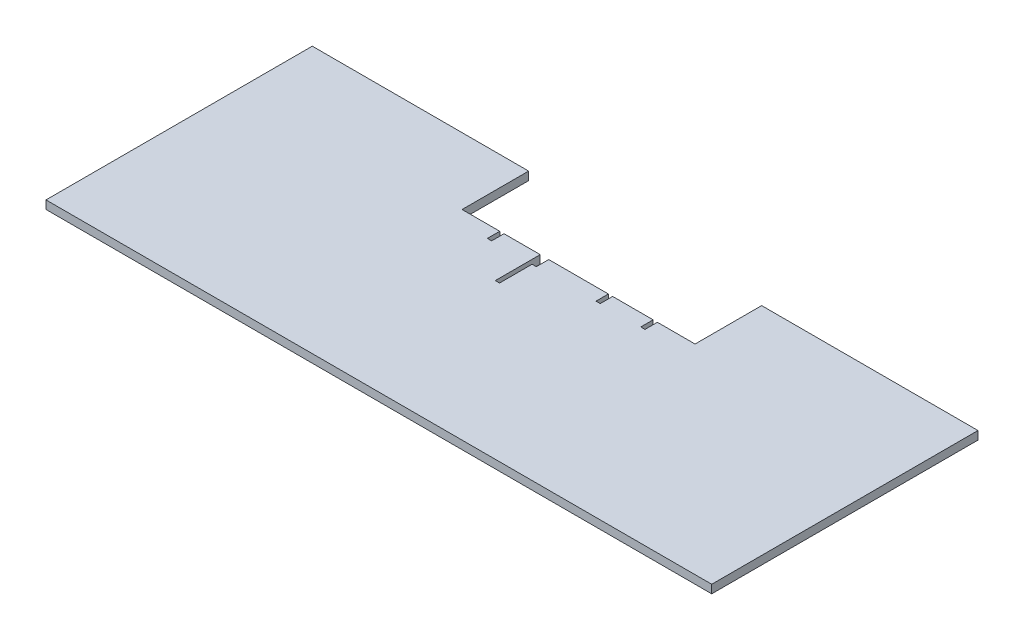
SolidWorks part; units mm, degrees
material "Depron"
ref_plane "Front Plane" through (0, 0, 0) normal (0, 0, 1) x (1, 0, 0)
ref_plane "Top Plane" through (0, 0, 0) normal (0, 1, 0) x (1, 0, 0)
ref_plane "Right Plane" through (0, 0, 0) normal (1, 0, 0) x (0, 0, -1)
sketch "Sketch1" plane through (0, 0, 0) normal (0, 1, 0) x (1, 0, 0)
  line L0 (171.45, 101.6) -> (254, 101.6)
  line L1 (0, 0) -> (254, 0)
  line L2 (0, 0) -> (0, 101.6)
  line L3 (0, 101.6) -> (82.55, 101.6)
  line L4 (254, 0) -> (254, 101.6)
  line L5 (127, -898.4) -> (127, 49101.6) construction
  line L6 (82.55, 101.6) -> (82.55, 76.2)
  line L7 (82.55, 76.2) -> (171.45, 76.2)
  line L8 (171.45, 101.6) -> (171.45, 76.2)
  point P9 (127, 101.6)
  point P10 (127, 101.6)
  point P11 (127, 76.2)
  point P13 (127, 0)
  dimension "D1" = 101.6
  dimension "D2" = 254
  dimension "D3" = 25.4
  dimension "D4" = 88.9
extrude "Boss-Extrude1" add sketch "Sketch1" along normal blind 3.175
sketch "Sketch2" plane through (0, 3.175, 0) normal (0, 1, 0) x (-1, 0, 0)
  line L0 (-127, 0) -> (-127, -112.41) construction
  line L1 (0, 0) -> (-254, 0) construction
  line L2 (-171.45, -76.2) -> (-82.55, -76.2) construction
  line L3 (-96.9297, -76.2) -> (-98.5553, -76.2)
  line L4 (-96.9297, -76.2) -> (-96.9297, -71.4756)
  line L5 (-96.9297, -71.4756) -> (-98.5553, -71.4756)
  line L6 (-98.5553, -76.2) -> (-98.5553, -71.4756)
  line L7 (-113.996, -76.2) -> (-115.6216, -76.2)
  line L9 (-113.996, -71.4756) -> (-115.6216, -71.4756)
  line L10 (-115.6216, -76.2) -> (-115.6216, -71.4756)
  line L11 (-138.3784, -76.2) -> (-138.3784, -71.4756)
  line L12 (-140.004, -71.4756) -> (-138.3784, -71.4756)
  line L13 (-140.004, -76.2) -> (-140.004, -71.4756)
  line L14 (-140.004, -76.2) -> (-138.3784, -76.2)
  line L15 (-155.4447, -76.2) -> (-155.4447, -71.4756)
  line L16 (-157.0703, -71.4756) -> (-155.4447, -71.4756)
  line L17 (-157.0703, -76.2) -> (-157.0703, -71.4756)
  line L18 (-157.0703, -76.2) -> (-155.4447, -76.2)
  line L20 (-113.996, -76.2) -> (-112.3704, -76.2)
  line L21 (-113.996, -71.4756) -> (-113.996, -59.055)
  line L22 (-113.996, -59.055) -> (-112.3704, -59.055)
  line L23 (-112.3704, -76.2) -> (-112.3704, -59.055)
  dimension "D1" = 1.6256
  dimension "D2" = 4.7244
  dimension "D3" = 1.6256
  dimension "D4" = 4.7244
  dimension "D5" = 1.6256
  dimension "D6" = 17.145
extrude "Cut-Extrude1" cut sketch "Sketch2" against normal up to next
ref_plane "Center Plane" through (127, 0, 0) normal (1, 0, 0) x (0, 0, -1)
